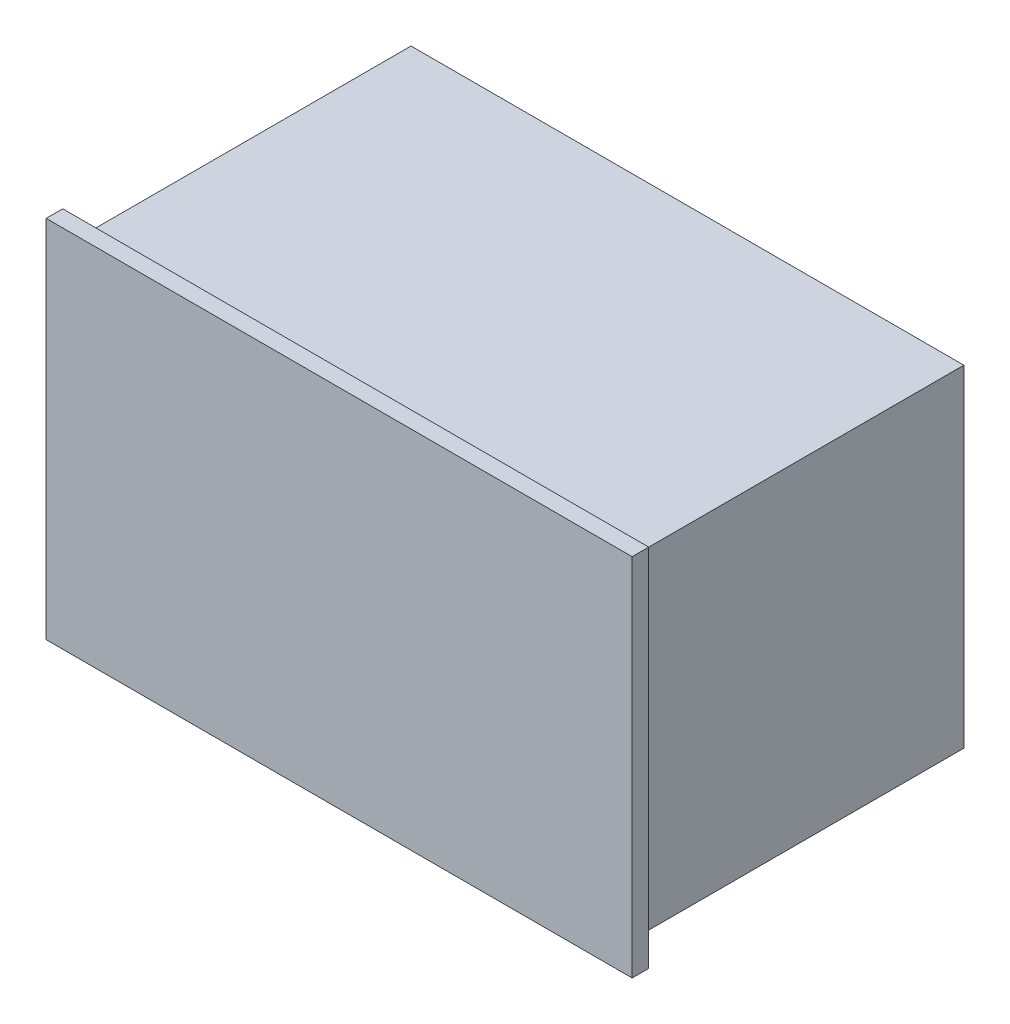
SolidWorks part; units mm, degrees
ref_plane "前视基准面" through (0, 0, 0) normal (0, 0, 1) x (1, 0, 0)
ref_plane "上视基准面" through (0, 0, 0) normal (0, 1, 0) x (1, 0, 0)
ref_plane "右视基准面" through (0, 0, 0) normal (1, 0, 0) x (0, 0, -1)
sketch "草图1" plane through (0, 0, 0) normal (0, 0, 1) x (1, 0, 0)
  line L1 (0, 0) -> (100, 0)
  line L2 (0, 0) -> (0, 60)
  line L3 (0, 60) -> (100, 60)
  line L4 (100, 0) -> (100, 60)
  dimension "D1" = 100
  dimension "D2" = 60
extrude "凸台-拉伸1" add sketch "草图1" along normal blind 60
sketch "草图2" plane through (0, 0, 60) normal (0, 0, 1) x (1, 0, 0)
  line L0 (0, 60) -> (0, 0) construction
  line L1 (3, 3) -> (97, 3)
  line L2 (3, 3) -> (3, 57)
  line L3 (3, 57) -> (97, 57)
  line L4 (97, 3) -> (97, 57)
  line L5 (0, 0) -> (100, 0) construction
  line L6 (100, 0) -> (100, 60) construction
  line L7 (100, 60) -> (0, 60) construction
  dimension "D1" = 3
  dimension "D2" = 3
  dimension "D3" = 3
  dimension "D4" = 3
extrude "切除-拉伸1" cut sketch "草图2" against normal blind 57
sketch "草图3" plane through (0, 0, 0) normal (0, -1, 0) x (1, 0, 0)
  line L0 (0, 20) -> (346.1653, 20) construction
sketch "草图4"
sketch "草图5" plane through (0, 0, 0) normal (-1, 0, 0) x (0, 0, 1)
  line L0 (-7.6667, -19.5) -> (-98.3333, -19.5) construction
sketch "草图6" plane through (100, 0, 0) normal (1, 0, 0) x (0, 0, -1)
  line L0 (7.6667, 79.5) -> (98.3333, 79.5) construction
sketch "草图8" plane through (0, 0, 0) normal (0, -1, 0) x (1, 0, 0)
  line L0 (0, 0) -> (100, 0) construction
  line L1 (0, 60) -> (0, 0) construction
  circle A0 centre (15, 12) radius 5.5
  circle A1 centre (30, 12) radius 5.5
  point P6 (0, 0)
  point P7 (0, 0)
  dimension "D1" = 11
  dimension "D2" = 11
  dimension "D3" = 12
  dimension "D4" = 15
  dimension "D5" = 15
extrude "切除-拉伸2" cut sketch "草图8" against normal up to next
sketch "草图9" plane through (0, 0, 60) normal (0, 0, 1) x (1, 0, 0)
  line L0 (0, 0) -> (100, 0) construction
  line L1 (-3, -3) -> (103, -3)
  line L2 (-3, -3) -> (-3, 63)
  line L3 (-3, 63) -> (103, 63)
  line L4 (103, -3) -> (103, 63)
  line L5 (100, 0) -> (100, 60) construction
  line L6 (0, 60) -> (0, 0) construction
  line L7 (100, 60) -> (0, 60) construction
  dimension "D1" = 3
  dimension "D2" = 3
  dimension "D3" = 3
  dimension "D4" = 3
extrude "凸台-拉伸2" add sketch "草图9" along normal blind 3
